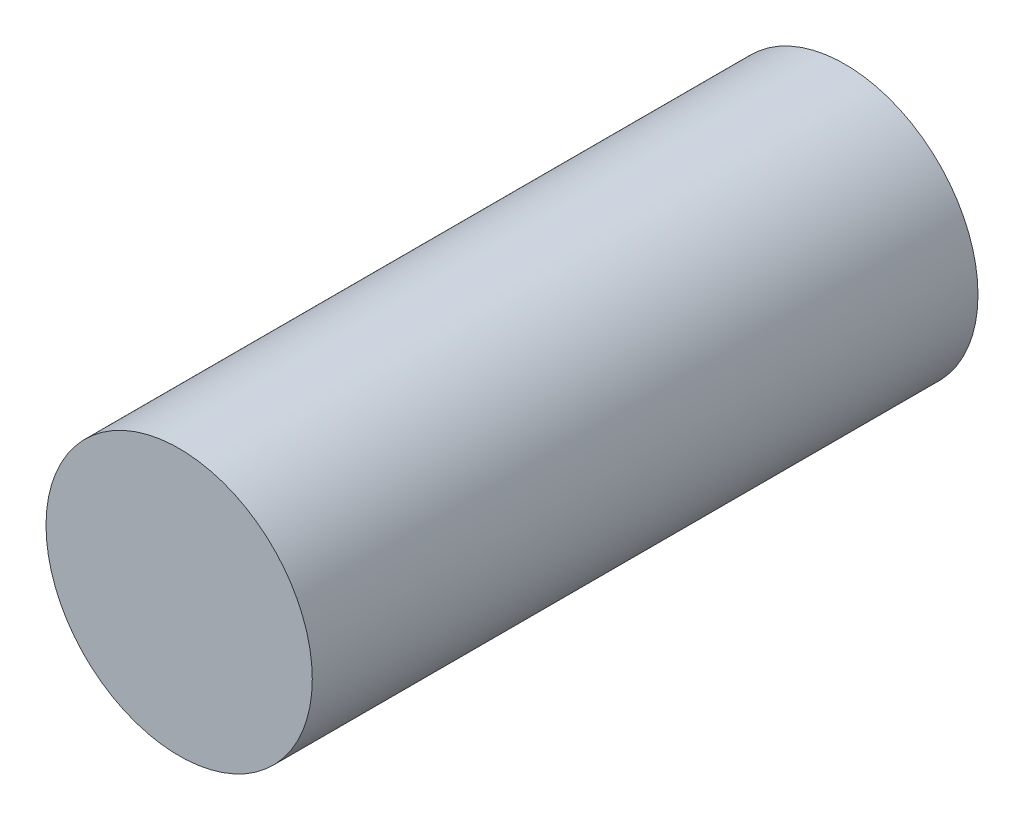
SolidWorks part; units mm, degrees
ref_plane "前视基准面" through (0, 0, 0) normal (0, 0, 1) x (1, 0, 0)
ref_plane "上视基准面" through (0, 0, 0) normal (0, 1, 0) x (1, 0, 0)
ref_plane "右视基准面" through (0, 0, 0) normal (1, 0, 0) x (0, 0, -1)
sketch "草图1" plane through (0, 0, 0) normal (0, 0, 1) x (1, 0, 0)
  circle A0 centre (0, 0) radius 5
  dimension "D1" = 10
extrude "凸台-拉伸1" add sketch "草图1" along normal blind 25
